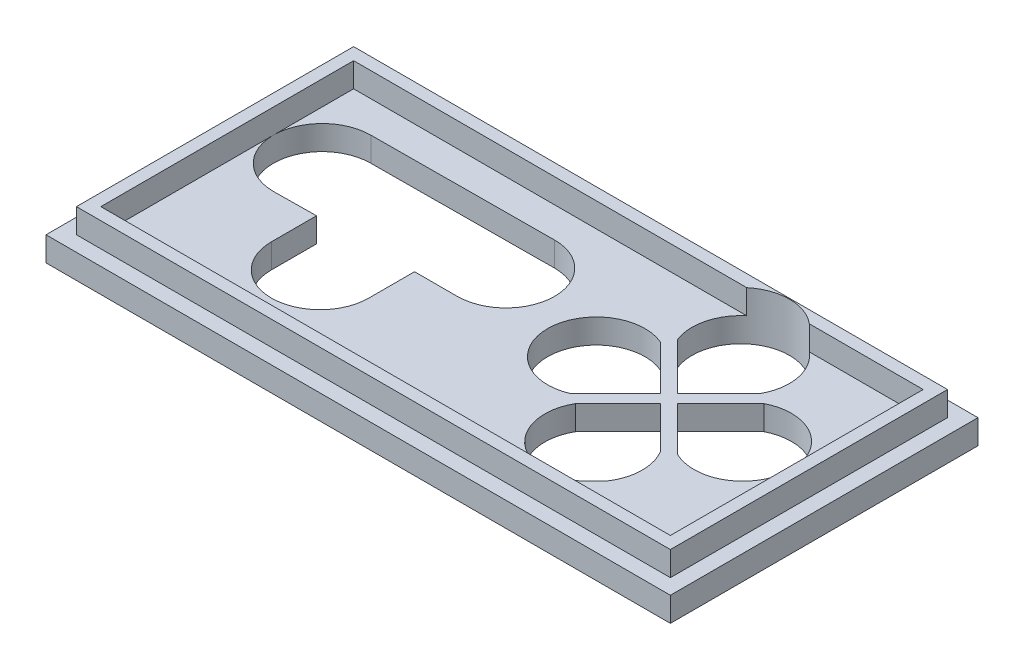
SolidWorks part; units mm, degrees
ref_plane "Front Plane" through (0, 0, 0) normal (0, 0, 1) x (1, 0, 0)
ref_plane "Top Plane" through (0, 0, 0) normal (0, 1, 0) x (1, 0, 0)
ref_plane "Right Plane" through (0, 0, 0) normal (1, 0, 0) x (0, 0, -1)
sketch "Sketch1" plane through (0, 0, 0) normal (0, 1, 0) x (1, 0, 0)
  line L1 (-48.75, -22.75) -> (48.75, -22.75)
  line L2 (-48.75, -22.75) -> (-48.75, 22.75)
  line L3 (-48.75, 22.75) -> (48.75, 22.75)
  line L4 (48.75, -22.75) -> (48.75, 22.75)
  line L5 (-48.75, -22.75) -> (48.75, 22.75) construction
  line L6 (-48.75, 22.75) -> (48.75, -22.75) construction
  line L7 (-46.75, -20.75) -> (46.75, -20.75)
  line L8 (-46.75, -20.75) -> (-46.75, 20.75)
  line L9 (-46.75, 20.75) -> (46.75, 20.75)
  line L10 (46.75, -20.75) -> (46.75, 20.75)
  line L11 (-46.75, -20.75) -> (46.75, 20.75) construction
  line L12 (-46.75, 20.75) -> (46.75, -20.75) construction
  point P0 (0, 0)
  point P6 (0, 0)
  point P11 (-46.75, 0)
  dimension "D1" = 97.5
  dimension "D2" = 45.5
  dimension "D3" = 2
  dimension "D4" = 2
extrude "Boss-Extrude1" add sketch "Sketch1" along normal blind 4
sketch "Sketch2" plane through (0, 0, 0) normal (0, -1, 0) x (-1, 0, 0)
  line L0 (48.75, -22.75) -> (-48.75, -22.75) construction
  line L1 (51.25, 25.25) -> (-51.25, 25.25)
  line L2 (51.25, 25.25) -> (51.25, -25.25)
  line L3 (51.25, -25.25) -> (-51.25, -25.25)
  line L4 (-51.25, 25.25) -> (-51.25, -25.25)
  line L5 (51.25, 25.25) -> (-51.25, -25.25) construction
  line L6 (51.25, -25.25) -> (-51.25, 25.25) construction
  line L7 (48.75, 22.75) -> (48.75, -22.75) construction
  point P0 (0, 0)
  dimension "D1" = 2.5
  dimension "D2" = 2.5
extrude "Boss-Extrude2" add sketch "Sketch2" along normal blind 4
sketch "Sketch3" plane through (0, -4, 0) normal (0, -1, 0) x (1, 0, 0)
  line L8 (11.1482, 8.0208) -> (15.6384, 12.5109)
  line L9 (27.6998, 16.3445) -> (29.733, 14.3113)
  line L10 (38.4741, -9.9081) -> (29.9702, -18.412)
  line L11 (15.4609, -17.5052) -> (7.7141, -9.7584)
  line L12 (11.1482, 8.0208) -> (21.7548, -2.5858)
  line L13 (12.5624, 9.435) -> (23.169, -1.1716)
  line L14 (34.1924, 9.8518) -> (23.169, -1.1716)
  line L15 (35.6067, 8.4376) -> (24.5832, -2.5858)
  line L16 (23.169, -4.0001) -> (33.7756, -14.6067)
  line L17 (24.5832, -2.5858) -> (35.1898, -13.1924)
  line L18 (21.7548, -2.5858) -> (11.1482, -13.1924)
  line L19 (23.169, -4.0001) -> (12.5624, -14.6067)
  line L21 (34.1924, 9.8518) -> (41.3807, 2.6636)
  line L37 (-38.75, 0.4229) -> (-31.75, 0.3422)
  line L38 (-16.25, 0.25) -> (-8.75, 0.25)
  line L39 (-31.75, 7.75) -> (-31.75, 0.3422)
  line L40 (-15.75, 7.75) -> (-15.75, 0.25)
  line L41 (-38.75, -15.5771) -> (-8.75, -15.75)
  arc A1 (-38.5656, 0.4208) -> (-38.75, -15.5771) centre (-38.75, -7.5771) ccw
  arc A3 (-8.8422, -15.7495) -> (-8.75, 0.25) centre (-8.75, -7.75) ccw
  arc A4 (-15.75, 7.75) -> (-31.75, 7.75) centre (-23.75, 7.75) ccw
  arc A5 (14.3963, 4.7726) -> (14.3963, -9.9443) centre (11.2574, -2.5858) ccw
  arc A6 (27.2089, 2.8683) -> (16.2088, 5.7886) centre (23.1516, 9.7631) ccw
  arc A7 (15.4829, -11.6862) -> (29.9292, -10.7603) centre (22.924, -14.6238) ccw
  arc A8 (31.6774, -9.68) -> (28.1369, 0.9679) centre (35.3186, -2.5567) ccw
  dimension "D28" = 16
  dimension "D31" = 16
  dimension "D7" = 16
  dimension "D8" = 16
  dimension "D9" = 16
  dimension "D10" = 16
  dimension "D1" = 2
  dimension "D2" = 2
  dimension "D3" = 32
  dimension "D5" = 15
  dimension "D6" = 15
extrude "Cut-Extrude1" cut sketch "Sketch3" against normal through all
